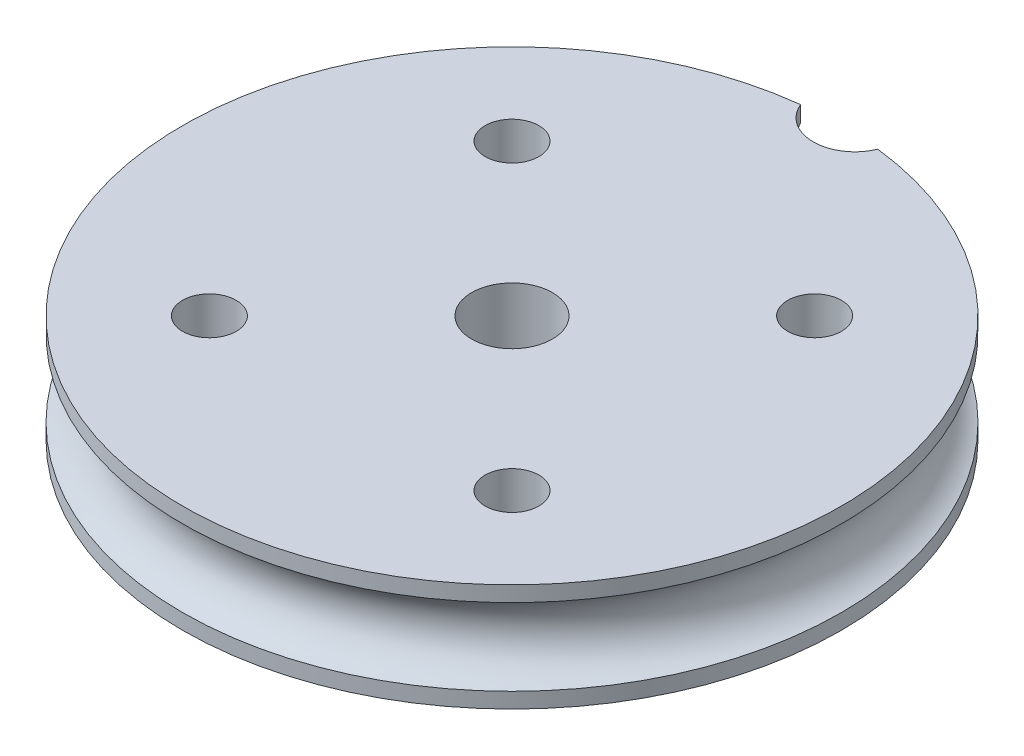
SolidWorks part; units mm, degrees
ref_plane "前视基准面" through (0, 0, 0) normal (0, 0, 1) x (1, 0, 0)
ref_plane "上视基准面" through (0, 0, 0) normal (0, 1, 0) x (1, 0, 0)
ref_plane "右视基准面" through (0, 0, 0) normal (1, 0, 0) x (0, 0, -1)
sketch "草图2" plane through (0, 0, 0) normal (0, 0, 1) x (1, 0, 0)
  line L0 (0, 8) -> (24.5, 8)
  line L1 (0, 0) -> (20, 0)
  line L2 (0, 0) -> (0, 8)
  line L3 (0, 8) -> (20, 8)
  line L5 (0, 8) -> (3, 8)
  line L6 (0, 8) -> (0, 0)
  line L7 (0, 0) -> (3, 0)
  line L8 (3, 8) -> (3, 0)
  line L9 (30, 8) -> (25.5, 8)
  line L11 (24.5, 0) -> (20, 0)
  line L12 (24.5, 1.0657) -> (24.5, 1.1451)
  line L13 (24.5, 0) -> (24.5, 1.0657)
  line L14 (24.5, 6.8549) -> (24.5, 6.9343)
  line L15 (25.5, 8) -> (30, 8)
  line L16 (24.5, 6.9343) -> (24.5, 8)
  arc A4 (24.5, 6.8549) -> (24.5, 1.1451) centre (25.5, 4) ccw
  point P4 (21, 3)
  dimension "D3" = 3
  dimension "D2" = 8
  dimension "D4" = 20
revolve "旋转1" add sketch "草图2" angle 360 about L2
sketch "草图3" plane through (0, 0, 0) normal (0, -1, 0) x (1, 0, 0)
  line L15 (1.836, -17.3501) -> (3.4084, -10.7985)
  line L17 (-1.836, -17.3501) -> (-3.4084, -10.7985)
  line L18 (-17.3501, 1.836) -> (-10.7985, 3.4084)
  line L19 (-17.3501, -1.836) -> (-10.7985, -3.4084)
  line L20 (1.836, 17.3501) -> (3.4084, 10.7985)
  line L21 (-1.836, 17.3501) -> (-3.4084, 10.7985)
  line L22 (17.3501, -1.836) -> (10.7985, -3.4084)
  line L23 (17.3501, 1.836) -> (10.7985, 3.4084)
  line L24 (-0.5274, -18.4925) -> (0.5274, -18.4925)
  line L26 (-18.4925, 0.5274) -> (-18.4925, -0.5274)
  line L28 (-0.5274, 18.4925) -> (0.5274, 18.4925)
  line L30 (18.4925, 0.5274) -> (18.4925, -0.5274)
  arc A13 (1.836, -17.3501) -> (0.5274, -18.4925) centre (0.3774, -17) cw
  arc A14 (-0.5274, -18.4925) -> (-1.836, -17.3501) centre (-0.3774, -17) cw
  arc A15 (-17.3501, -1.836) -> (-18.4925, -0.5274) centre (-17, -0.3774) cw
  arc A16 (-18.4925, 0.5274) -> (-17.3501, 1.836) centre (-17, 0.3774) cw
  arc A17 (-1.836, 17.3501) -> (-0.5274, 18.4925) centre (-0.3774, 17) cw
  arc A18 (0.5274, 18.4925) -> (1.836, 17.3501) centre (0.3774, 17) cw
  arc A19 (17.3501, 1.836) -> (18.4925, 0.5274) centre (17, 0.3774) cw
  arc A20 (18.4925, -0.5274) -> (17.3501, -1.836) centre (17, -0.3774) cw
  arc A21 (-3.4084, -10.7985) -> (-10.7985, -3.4084) centre (-13.1322, -13.1322) ccw
  arc A22 (3.4084, -10.7985) -> (10.7985, -3.4084) centre (13.1322, -13.1322) cw
  arc A23 (3.4084, 10.7985) -> (10.7985, 3.4084) centre (13.1322, 13.1322) ccw
  arc A24 (-3.4084, 10.7985) -> (-10.7985, 3.4084) centre (-13.1322, 13.1322) cw
  circle A25 centre (0, 0) radius 3
  point P18 (0, 0)
  point P58 (0, 0)
  point P85 (0, 0)
  dimension "D1" = 10
  dimension "D2" = 4
  dimension "D5" = 1.5
  dimension "D4" = 4
extrude "切除-拉伸1" cut sketch "草图3" against normal blind 2.5
sketch "草图4" plane through (0, 0, 0) normal (0, -1, 0) x (1, 0, 0)
  line L34 (7.0931, 11.25) -> (9.1715, 7.65)
  line L35 (-11.25, 11.25) -> (11.25, 11.25)
  line L76 (-11.25, 11.25) -> (-11.25, -11.25)
  line L83 (-11.25, -11.25) -> (11.25, -11.25)
  line L90 (11.25, 11.25) -> (11.25, -11.25)
  line L97 (-11.25, 11.25) -> (11.25, -11.25) construction
  line L98 (-11.25, -11.25) -> (11.25, 11.25) construction
  line L99 (-11.25, 7.0931) -> (-7.65, 9.1715)
  line L100 (-7.65, 9.1715) -> (-7.65, 13.3285)
  line L101 (-7.65, 13.3285) -> (-11.25, 15.4069)
  line L102 (-11.25, 15.4069) -> (-14.85, 13.3285)
  line L103 (-14.85, 13.3285) -> (-14.85, 9.1715)
  line L104 (-14.85, 9.1715) -> (-11.25, 7.0931)
  line L105 (9.1715, 7.65) -> (13.3285, 7.65)
  line L106 (13.3285, 7.65) -> (15.4069, 11.25)
  line L107 (15.4069, 11.25) -> (13.3285, 14.85)
  line L108 (13.3285, 14.85) -> (9.1715, 14.85)
  line L109 (9.1715, 14.85) -> (7.0931, 11.25)
  line L110 (11.25, -7.0931) -> (7.65, -9.1715)
  line L111 (7.65, -9.1715) -> (7.65, -13.3285)
  line L112 (7.65, -13.3285) -> (11.25, -15.4069)
  line L113 (11.25, -15.4069) -> (14.85, -13.3285)
  line L114 (14.85, -13.3285) -> (14.85, -9.1715)
  line L115 (14.85, -9.1715) -> (11.25, -7.0931)
  line L116 (-7.0931, -11.25) -> (-9.1715, -7.65)
  line L117 (-9.1715, -7.65) -> (-13.3285, -7.65)
  line L118 (-13.3285, -7.65) -> (-15.4069, -11.25)
  line L119 (-15.4069, -11.25) -> (-13.3285, -14.85)
  line L120 (-13.3285, -14.85) -> (-9.1715, -14.85)
  line L121 (-9.1715, -14.85) -> (-7.0931, -11.25)
  circle A0 centre (-11.25, 11.25) radius 3.6 construction
  point P0 (-3.4771, -2.0075)
  point P1 (0, 0)
  point P34 (0, 0)
extrude "切除-拉伸2" cut sketch "草图4" against normal blind 3
sketch "草图6" plane through (0, 3, 0) normal (0, -1, 0) x (1, 0, 0)
  line L1 (-11.25, -11.25) -> (11.25, -11.25)
  line L2 (-11.25, -11.25) -> (-11.25, 11.25)
  line L3 (-11.25, 11.25) -> (11.25, 11.25)
  line L4 (11.25, -11.25) -> (11.25, 11.25)
  line L5 (-11.25, -11.25) -> (11.25, 11.25) construction
  line L6 (-11.25, 11.25) -> (11.25, -11.25) construction
  circle A0 centre (-11.25, 11.25) radius 2
  circle A1 centre (11.25, 11.25) radius 2
  circle A2 centre (11.25, -11.25) radius 2
  circle A3 centre (-11.25, -11.25) radius 2
  point P0 (0, 0)
  point P16 (0, 0)
  dimension "D1" = 22.5
extrude "切除-拉伸4" cut sketch "草图6" against normal through all contours A0 | A1 | A3 | A2
sketch "草图8" plane through (0, 8, 0) normal (0, 1, 0) x (1, 0, 0)
  circle A1 centre (0, 25.5) radius 3.1
  point P0 (0, 25.5)
  dimension "D2" = 6.2
  dimension "D1" = 25.5
extrude "切除-拉伸6" cut sketch "草图8" against normal blind 5 contours A1
